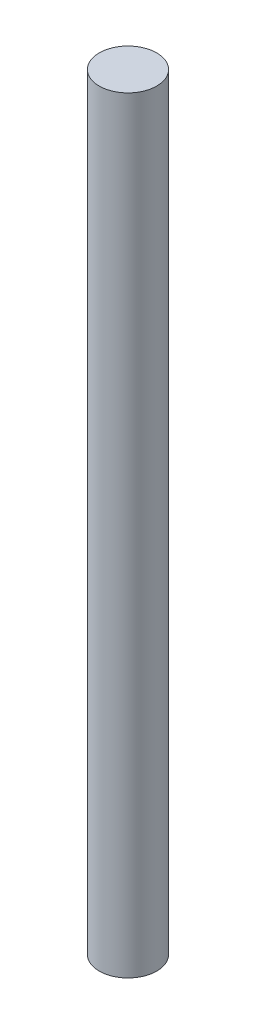
SolidWorks part; units mm, degrees
ref_plane "Plan de face" through (0, 0, 0) normal (0, 0, 1) x (1, 0, 0)
ref_plane "Plan de dessus" through (0, 0, 0) normal (0, 1, 0) x (1, 0, 0)
ref_plane "Plan de droite" through (0, 0, 0) normal (1, 0, 0) x (0, 0, -1)
sketch "Sketch1" plane through (0, 0, 0) normal (0, 1, 0) x (1, 0, 0)
  circle A0 centre (0, 0) radius 1.5
extrude "Boss-Extrude1" add sketch "Sketch1" along normal blind 40
